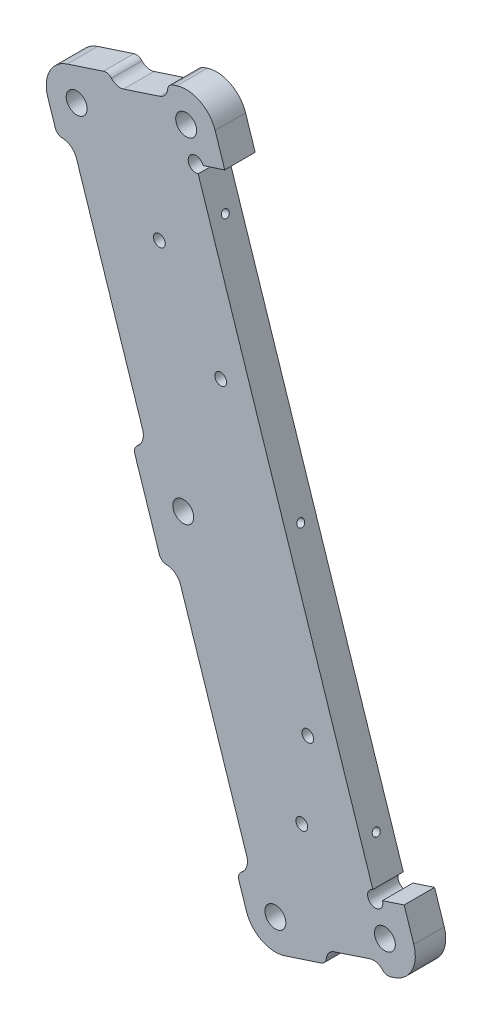
SolidWorks part; units mm, degrees
material "Beech"
ref_plane "Front Plane" through (0, 0, 0) normal (0, 0, 1) x (1, 0, 0)
ref_plane "Top Plane" through (0, 0, 0) normal (0, 1, 0) x (1, 0, 0)
ref_plane "Right Plane" through (0, 0, 0) normal (1, 0, 0) x (0, 0, -1)
sketch "Sketch1" plane through (0, 0, 0) normal (0, 0, 1) x (1, 0, 0)
  line L0 (-562.3045, 806.2321) -> (-471.5395, 529.5387)
  line L1 (-562.3045, 806.2321) -> (-504.5869, 825.1655)
  line L2 (-471.5395, 529.5387) -> (-413.8219, 548.4721)
  line L3 (-504.5869, 825.1655) -> (-413.8219, 548.4721)
  line L6 (-496.6075, 800.8407) -> (-484.5402, 804.7992) construction
  line L7 (-496.6075, 800.8407) -> (-491.0076, 783.7696) construction
  line L8 (-421.8012, 572.7968) -> (-409.7339, 576.7553) construction
  line L9 (-504.5869, 825.1655) -> (-496.6075, 800.8407)
  line L10 (-504.5869, 825.1655) -> (-492.5196, 829.124)
  line L11 (-496.6075, 800.8407) -> (-484.5402, 804.7992)
  line L12 (-492.5196, 829.124) -> (-484.5402, 804.7992)
  line L13 (-413.8219, 548.4721) -> (-421.8012, 572.7968)
  line L14 (-413.8219, 548.4721) -> (-401.7546, 552.4306)
  line L15 (-421.8012, 572.7968) -> (-409.7339, 576.7553)
  line L16 (-401.7546, 552.4306) -> (-409.7339, 576.7553)
  dimension "D1" = 60.7437
  dimension "D2" = 25.6001
  dimension "D3" = 25.6001
extrude "Boss-Extrude1" add sketch "Sketch1" along normal blind 12.7 contours L3 L1 L0 L2 | L14 L16 L15 L3 | L10 L12 L11 L9
fillet "Fillet1" radius 12.7 4 edges at (-471.5395, 529.5387, 6.35) (-562.3045, 806.2321, 6.35) (-401.7546, 552.4306, 6.35) (-492.5196, 829.124, 6.35)
hole_wizard "1/4 (0.25) Diameter Hole1" positions "Sketch2" profile "Sketch3" hole size "1/4" standard "ANSI Inch" end condition through all
sketch "Sketch2" plane through (0, 0, 0) normal (0, 0, -1) x (-1, 0, 0)
  point P0 (496.6075, 800.8407)
  point P3 (421.8012, 572.7968)
sketch "Sketch3" plane through (-496.6075, 800.8407, 0) normal (1, 0, 0) x (0, 1, 0)
  line L0 (0, 0) -> (0, 12.7)
  line L1 (0, 12.7) -> (3.175, 12.7)
  line L2 (3.175, 12.7) -> (3.175, 0)
  line L5 (3.175, 0) -> (0, 0)
  line L11 (0, -6.35) -> (0, 107.95) construction
  dimension "Thru Hole Dia." = 6.35
  dimension "Thru Hole Depth" = 12.7
hole_wizard "Hole1" positions "Sketch4" profile "Sketch5" legacy
sketch "Sketch4" plane through (-72.822, -450.3066, -91.075) normal (0.9502, 0.3117, 0) x (0, 0, -1)
  line L0 (-97.425, 1320.9097) -> (-97.425, 1080.9097) construction
  point P9 (-97.425, 1301.8597)
  point P11 (-97.425, 1200.9097)
  point P13 (-97.425, 1099.9597)
sketch "Sketch5" plane through (-415.6717, 594.8563, 6.35) normal (0, 0, 1) x (-0.3117, 0.9502, 0)
  line L0 (0, 0) -> (0, 39.0539)
  line L1 (0, 39.0539) -> (1.5875, 38.1)
  line L2 (1.5875, 38.1) -> (1.5875, 4.0177)
  line L3 (1.5875, 4.0177) -> (5.08, 0)
  line L4 (5.08, 0) -> (0, 0)
  line L5 (0, -14.3089) -> (0, 102.4216) construction
  line L6 (0, 39.0539) -> (-1.5875, 38.1) construction
  line L7 (-1.5875, 4.0177) -> (-5.08, 0) construction
  dimension "Diameter" = 3.175
  dimension "Depth" = 38.1
  dimension "C-Sink Diameter" = 10.16
  dimension "C-Sink Angle" = 82
  dimension "Drill Angle" = 118
hole_wizard "5/16 Clearance Hole1" positions "Sketch8" profile "Sketch7" hole size "5/16" standard "ANSI Inch" end condition through all
sketch "Sketch8" plane through (0, 0, 12.7) normal (0, 0, 1) x (1, 0, 0)
  point P0 (-546.2786, 798.1233)
  point P3 (-500.6284, 813.0982)
  point P6 (-463.4306, 545.5646)
  point P9 (-417.7804, 560.5394)
  point P13 (-501.8378, 672.8336)
sketch "Sketch7" plane through (-546.2786, 798.1233, 12.7) normal (1, 0, 0) x (0, -1, 0)
  line L0 (0, 0) -> (0, 12.7)
  line L1 (0, 12.7) -> (4.365, 12.7)
  line L2 (4.365, 12.7) -> (4.365, 0)
  line L5 (4.365, 0) -> (0, 0)
  line L11 (0, -6.35) -> (0, 107.95) construction
  dimension "Thru Hole Dia." = 8.73
  dimension "Thru Hole Depth" = 12.7
sketch "Sketch9" plane through (0, 0, 12.7) normal (0, 0, 1) x (1, 0, 0)
  line L0 (-528.2109, 817.416) -> (-513.1267, 822.3641) construction
  line L1 (-550.2371, 810.1906) -> (-504.5869, 825.1655) construction
  line L2 (-529.6953, 821.9412) -> (-514.6111, 826.8894)
  line L3 (-526.7264, 812.8907) -> (-511.6423, 817.8389)
  line L4 (-526.4391, 796.7354) -> (-532.7361, 815.9316) construction
  line L5 (-516.922, 667.8854) -> (-447.1371, 690.7773) construction
  line L6 (-558.346, 794.1648) -> (-475.498, 541.6061) construction
  line L7 (-488.5611, 817.0567) -> (-484.5402, 804.7992) construction
  line L8 (-552.4082, 776.0638) -> (-524.839, 692.0201) construction
  line L9 (-546.3746, 778.0431) -> (-518.8053, 693.9993)
  line L10 (-558.4419, 774.0846) -> (-530.8726, 690.0408)
  line L13 (-437.4458, 540.7226) -> (-422.3617, 545.6708) construction
  line L14 (-435.9614, 536.1974) -> (-420.8773, 541.1455)
  line L15 (-438.9303, 545.2479) -> (-423.8461, 550.196)
  line L16 (-481.4357, 559.7071) -> (-509.005, 643.7508) construction
  line L17 (-475.402, 561.6863) -> (-502.9713, 645.73)
  line L18 (-487.4694, 557.7278) -> (-515.0386, 641.7715)
  arc A0 (-529.6953, 821.9412) -> (-526.7264, 812.8907) centre (-528.2109, 817.416) ccw
  arc A1 (-511.6423, 817.8389) -> (-514.6111, 826.8894) centre (-513.1267, 822.3641) ccw
  arc A2 (-435.9614, 536.1974) -> (-438.9303, 545.2479) centre (-437.4458, 540.7226) cw
  arc A3 (-546.3746, 778.0431) -> (-558.4419, 774.0846) centre (-552.4082, 776.0638) ccw
  arc A4 (-530.8726, 690.0408) -> (-518.8053, 693.9993) centre (-524.839, 692.0201) ccw
  arc A5 (-423.8461, 550.196) -> (-420.8773, 541.1455) centre (-422.3617, 545.6708) cw
  arc A6 (-475.402, 561.6863) -> (-487.4694, 557.7278) centre (-481.4357, 559.7071) cw
  arc A7 (-515.0386, 641.7715) -> (-502.9713, 645.73) centre (-509.005, 643.7508) cw
  point P4 (-520.6688, 819.8901)
  point P9 (-532.7361, 815.9316)
  point P10 (-508.6015, 823.8486)
  point P11 (-538.6236, 734.0419)
  point P29 (-429.9038, 543.1967)
  point P36 (-495.2203, 601.7289)
  dimension "D2" = 9.525
  dimension "D1" = 25.4
  dimension "D3" = 12.7
  dimension "D4" = 25.4
  dimension "D5" = 31.75
extrude "Cut-Extrude1" cut sketch "Sketch9" against normal through all
fillet "Fillet2" radius 3.175 8 edges at (-508.6015, 823.8486, 6.35) (-532.7361, 815.9316, 6.35) (-417.8364, 547.1552, 6.35) (-441.9711, 539.2382, 6.35) (-479.4565, 553.6734, 6.35) (-510.9842, 649.7844, 6.35) (-522.8597, 685.9864, 6.35) (-554.3875, 782.0975, 6.35)
hole_wizard "Hole2" positions "Sketch10" profile "Sketch11" legacy
sketch "Sketch10" plane through (322.2568, -320.707, 0.268) normal (0, 0, 1) x (0.9978, -0.0669, 0)
  point P1 (-659.7862, 411.7841)
  point P3 (-615.2409, 429.7815)
  point P5 (-711.4987, 766.922)
  point P7 (-796.2804, 732.668)
  point P9 (-889.1694, 1044.5267)
  point P11 (-923.7091, 1031.114)
sketch "Sketch11" plane through (-308.4809, 134.3246, 0.268) normal (1, 0, 0) x (0, -1, 0)
  line L0 (0, 0) -> (0, 39.0539)
  line L1 (0, 39.0539) -> (1.5875, 38.1)
  line L2 (1.5875, 38.1) -> (1.5875, 4.0177)
  line L3 (1.5875, 4.0177) -> (5.08, 0)
  line L4 (5.08, 0) -> (0, 0)
  line L5 (0, -14.3089) -> (0, 102.4216) construction
  line L6 (0, 39.0539) -> (-1.5875, 38.1) construction
  line L7 (-1.5875, 4.0177) -> (-5.08, 0) construction
  dimension "Diameter" = 3.175
  dimension "Depth" = 38.1
  dimension "C-Sink Diameter" = 10.16
  dimension "C-Sink Angle" = 82
  dimension "Drill Angle" = 118
hole_wizard "CSK for #8 Flat Head Machine Screw (100)2" positions "Sketch14" profile "Sketch15" countersink size "#8" standard "ANSI Inch"
sketch "Sketch14" plane through (322.2568, -320.707, 0) normal (0, 0, -1) x (-0.9978, 0.0669, 0)
  line L0 (876.907, 992.6723) -> (833.2652, 884.6552) construction
  line L2 (855.0861, 938.6638) -> (866.8613, 933.9062) construction
  line L4 (904.9214, 1028.1081) -> (833.5588, 851.4796) construction
  point P2 (833.2652, 884.6552)
  point P8 (904.9214, 1028.1081)
  point P9 (833.5588, 851.4796)
  point P10 (876.907, 992.6723)
sketch "Sketch15" plane through (-486.2252, 728.4455, 0) normal (1, 0, 0) x (0, 1, 0)
  line L0 (0, 0) -> (0, 23.7016)
  line L1 (0, 23.7016) -> (2.4574, 22.225)
  line L2 (2.4574, 22.225) -> (2.4574, 4.6509)
  line L3 (2.4574, 4.6509) -> (8.0002, 0)
  line L4 (8.0002, 0) -> (0, 0)
  line L5 (-2.4574, 4.6509) -> (-8.0002, 0) construction
  line L6 (0, 23.7016) -> (-2.4574, 22.225) construction
  line L7 (0, -6.35) -> (0, 107.95) construction
  dimension "Hole Dia." = 4.9149
  dimension "Hole Depth" = 22.225
  dimension "Near C'Sink Dia." = 16.0005
  dimension "Near C'Sink Angle" = 100
  dimension "Drill Angle" = 118
equation "\"D3@Sketch1\"=\"D2@Sketch1\""
